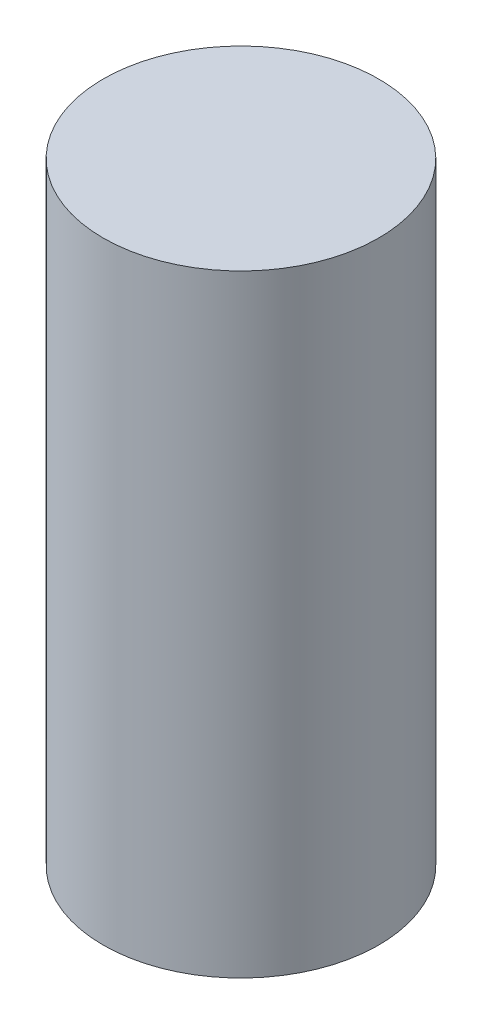
SolidWorks part; units mm, degrees
ref_plane "Front Plane" through (0, 0, 0) normal (0, 0, 1) x (1, 0, 0)
ref_plane "Top Plane" through (0, 0, 0) normal (0, 1, 0) x (1, 0, 0)
ref_plane "Right Plane" through (0, 0, 0) normal (1, 0, 0) x (0, 0, -1)
sketch "Sketch1" plane through (0, 0, 0) normal (0, 1, 0) x (1, 0, 0)
  circle A0 centre (0, 0) radius 9
  dimension "D1" = 18
extrude "Boss-Extrude1" add sketch "Sketch1" along normal blind 40
